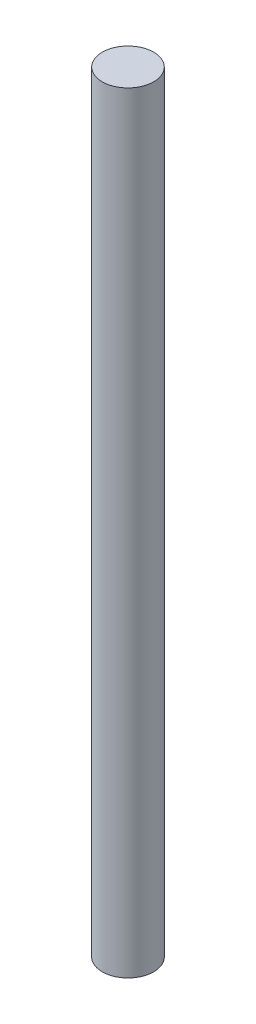
SolidWorks part; units mm, degrees
ref_plane "Front Plane" through (0, 0, 0) normal (0, 0, 1) x (1, 0, 0)
ref_plane "Top Plane" through (0, 0, 0) normal (0, 1, 0) x (1, 0, 0)
ref_plane "Right Plane" through (0, 0, 0) normal (1, 0, 0) x (0, 0, -1)
sketch "Sketch1" plane through (0, 0, 0) normal (0, 1, 0) x (1, 0, 0)
  circle A0 centre (0, 0) radius 4
extrude "Boss-Extrude1" add sketch "Sketch1" along normal blind 120
sketch "Sketch2" plane through (0, 120, 0) normal (0, 1, 0) x (1, 0, 0)
  circle A0 centre (0, 0) radius 6
